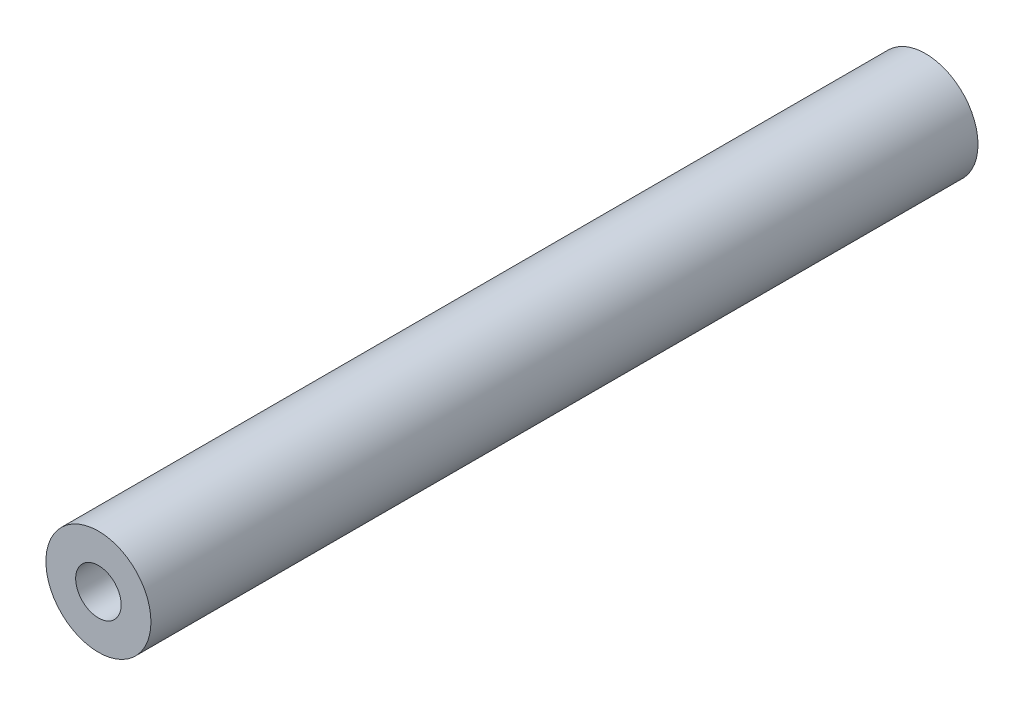
SolidWorks part; units mm, degrees
ref_plane "Piano frontale" through (0, 0, 0) normal (0, 0, 1) x (1, 0, 0)
ref_plane "Piano superiore" through (0, 0, 0) normal (0, 1, 0) x (1, 0, 0)
ref_plane "Piano destro" through (0, 0, 0) normal (1, 0, 0) x (0, 0, -1)
sketch "Schizzo1" plane through (0, 0, 0) normal (0, 0, 1) x (1, 0, 0)
  circle A0 centre (0, 0) radius 1.5875
  dimension "D1" = 3.175
extrude "Estrusione-Sottile1" add sketch "Schizzo1" along normal blind 25 thin thin type one direction reverse wall 0.9
